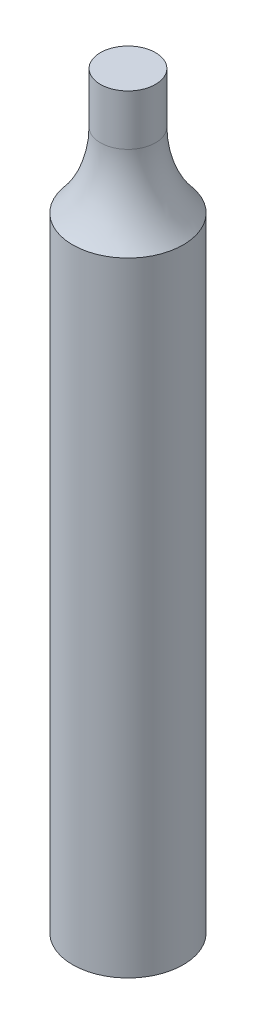
SolidWorks part; units mm, degrees
ref_plane "Front Plane" through (0, 0, 0) normal (0, 0, 1) x (1, 0, 0)
ref_plane "Top Plane" through (0, 0, 0) normal (0, 1, 0) x (1, 0, 0)
ref_plane "Right Plane" through (0, 0, 0) normal (1, 0, 0) x (0, 0, -1)
sketch "Sketch1" plane through (0, 0, 0) normal (1, 0, 0) x (0, 0, -1)
  line L0 (-16.287, 15.1559) -> (-16.287, -126.6672)
  line L1 (-16.287, -126.6672) -> (-26.7639, -126.6672)
  line L2 (-26.7639, -126.6672) -> (-26.7639, -8.5472)
  line L3 (-16.287, 15.1559) -> (-21.5037, 15.1559)
  line L4 (-21.5037, 15.1559) -> (-21.5037, 5.5702)
  arc A1 (-21.5037, 5.5702) -> (-26.7639, -8.5472) centre (-43.0778, 5.5702) cw
  point P7 (-8.5496, 27.333)
  point P8 (-5.3767, -70.1356)
  point P9 (0, 0)
  point P10 (4.8859, -103.5747)
  point P11 (-3.5573, 15.1559)
  point P12 (-15.753, -102.3117)
  point P13 (-26.7639, -103.2507)
  point P14 (-16.287, -126.6672)
revolve "Revolve3" add sketch "Sketch1" angle 360 about L0
